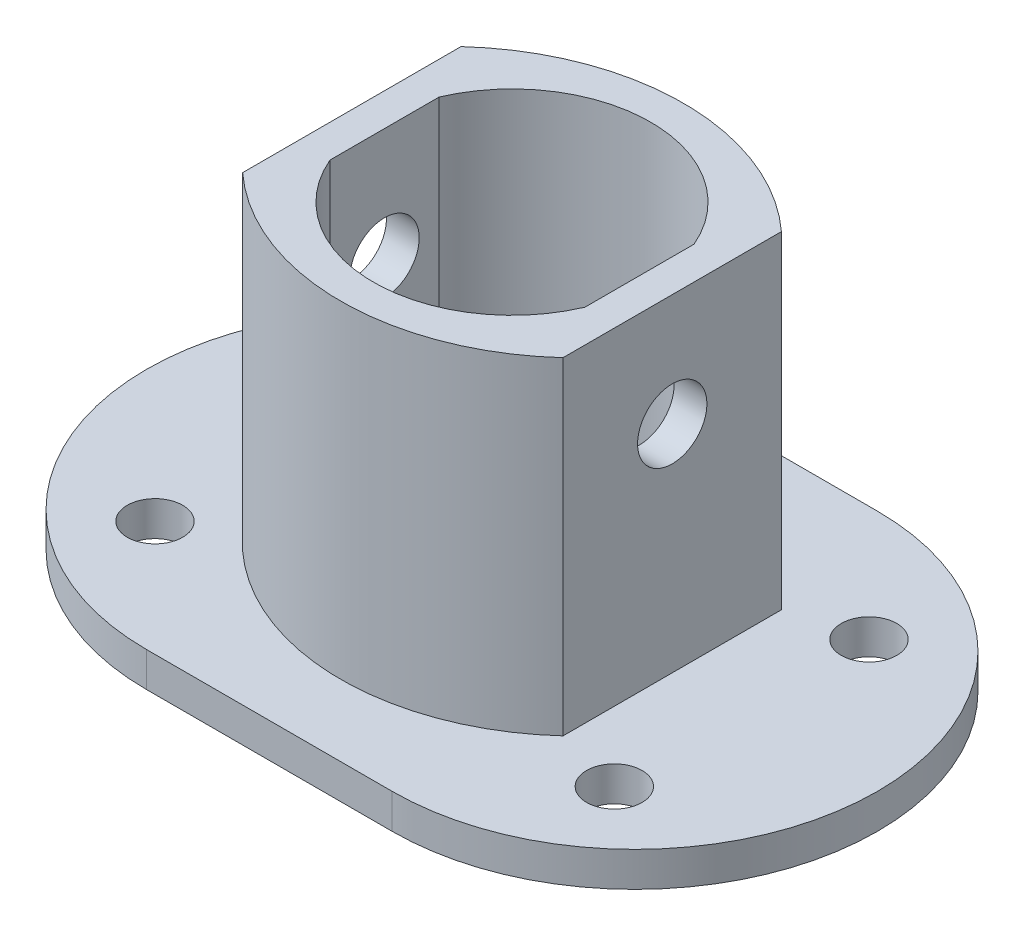
SolidWorks part; units mm, degrees
material "6061-T6 (SS)"
ref_plane "Front Plane" through (0, 0, 0) normal (0, 0, 1) x (1, 0, 0)
ref_plane "Top Plane" through (0, 0, 0) normal (0, 1, 0) x (1, 0, 0)
ref_plane "Right Plane" through (0, 0, 0) normal (1, 0, 0) x (0, 0, -1)
sketch "Sketch1" plane through (0, 0, 0) normal (0, 1, 0) x (1, 0, 0)
  line L0 (-11.25, 0) -> (11.25, 0) construction
  line L5 (-11.25, 22.225) -> (11.25, 22.225)
  line L6 (-11.25, -22.225) -> (11.25, -22.225)
  line L7 (-11.25, 22.225) -> (-11.25, -22.225) construction
  line L8 (11.25, 22.225) -> (11.25, -22.225) construction
  arc A0 (-11.25, 22.225) -> (-11.25, -22.225) centre (-11.25, 0) ccw
  arc A1 (11.25, -22.225) -> (11.25, 22.225) centre (11.25, 0) ccw
  point P2 (0, 0)
  dimension "D1" = 22.225
  dimension "D2" = 22.5
extrude "Boss-Extrude1" add sketch "Sketch1" along normal blind 3.175
sketch "Sketch2" plane through (0, 3.175, 0) normal (0, 1, 0) x (1, 0, 0)
  line L0 (-11.25, 22.225) -> (-11.25, -22.225) construction
  line L1 (-33.475, 0) -> (-26.475, 0) construction
  line L2 (-21.0364, -11.663) -> (-11.25, 0) construction
  line L3 (-11.25, 0) -> (-21.0364, 11.663) construction
  line L4 (0, 0) -> (0, 22.225) construction
  arc A0 (-11.25, 15.225) -> (-11.25, -15.225) centre (-11.25, 0) ccw construction
  arc A1 (-11.25, 22.225) -> (-11.25, -22.225) centre (-11.25, 0) ccw construction
  circle A2 centre (-21.0364, -11.663) radius 2.54
  circle A4 centre (-21.0364, 11.663) radius 2.54
  circle A6 centre (21.0364, -11.663) radius 2.54
  circle A7 centre (21.0364, 11.663) radius 2.54
  dimension "D2" = 5.08
  dimension "D1" = 7
  dimension "D3" = 100
extrude "Cut-Extrude1" cut sketch "Sketch2" against normal through all
sketch "Sketch3" plane through (0, 3.175, 0) normal (0, 1, 0) x (1, 0, 0)
  line L0 (-11.6743, 5) -> (-11.6743, -5)
  line L1 (-14.6743, 5.5816) -> (-14.6743, -5.5816) construction
  line L2 (-14.6743, 0) -> (-11.6743, 0) construction
  line L3 (0, 15.7) -> (0, 12.7) construction
  line L4 (-14.6743, -10) -> (-14.6743, 10)
  line L5 (14.6743, -10) -> (14.6743, 10)
  line L6 (11.6743, -5) -> (11.6743, 5)
  line L7 (11.6743, 0) -> (14.6743, 0) construction
  arc A0 (-14.6743, 5.5816) -> (-14.6743, -5.5816) centre (0, 0) ccw construction
  arc A1 (-11.6743, -5) -> (11.6743, -5) centre (0, 0) ccw
  arc A3 (11.6743, 5) -> (-11.6743, 5) centre (0, 0) ccw
  arc A4 (-14.6743, -10) -> (14.6743, -10) centre (0, 6.0391) ccw
  arc A5 (-14.6743, 10) -> (14.6743, 10) centre (0, -6.0391) cw
  point P13 (-14.6743, 0)
  dimension "D2" = 3
  dimension "D1" = 25.4
  dimension "D3" = 10
  dimension "D4" = 20
extrude "Boss-Extrude2" add sketch "Sketch3" along normal blind 30
sketch "Sketch4" plane through (0, 3.175, 0) normal (0, 1, 0) x (1, 0, 0)
  circle A0 centre (0, 0) radius 6.35
  dimension "D1" = 12.7
extrude "Cut-Extrude2" cut sketch "Sketch4" against normal through all
sketch "Sketch6" plane through (-14.6743, 2.2474, 9.5309) normal (-1, 0, 0) x (0, 0, 1)
  line L0 (-19.5309, 30.9276) -> (0.4691, 30.9276) construction
  circle A2 centre (-9.5309, 20.6776) radius 3.175
  point P5 (-9.5309, 30.9276)
  dimension "D1" = 10.25
  dimension "D2" = 6.35
extrude "Cut-Extrude3" cut sketch "Sketch6" against normal through all
sketch "Sketch8" plane through (0, 15.875, 0) normal (-1, 0, 0) x (0, 1, 0)
  line L0 (-12.7, 22.225) -> (2.3, 0)
  line L1 (-12.7, -22.225) -> (-12.7, 22.225) construction
  line L2 (2.3, 0) -> (2.3, -10)
  line L3 (2.3, -10) -> (-12.7, -10)
  line L4 (-12.7, 22.225) -> (-15.875, 22.225) construction
  line L6 (-12.7, -10) -> (-12.7, 22.225)
  line L10 (17.3, -15.7) -> (17.3, -10) construction
  line L12 (17.3, -10) -> (-12.7, -10) construction
  dimension "D2" = 10
  dimension "D3" = 15
extrude "Boss-Extrude3" [suppressed] add sketch "Sketch8" along normal mid plane 20
sketch "Sketch10" [suppressed] plane through (0, 18.175, 0) normal (0, 1, 0) x (0, 0, -1)
  line L1 (14.6743, 5) -> (24.6743, 5)
  line L2 (14.6743, 5) -> (14.6743, -5)
  line L3 (14.6743, -5) -> (24.6743, -5)
  line L4 (24.6743, 5) -> (24.6743, -5)
  line L7 (24.6743, 10) -> (24.6743, -10) construction
  line L8 (14.6743, -10) -> (24.6743, -10) construction
  line L9 (14.6743, -10) -> (14.6743, 10) construction
  dimension "D1" = 10
  dimension "D2" = 5
extrude "Cut-Extrude4" [suppressed] cut sketch "Sketch10" against normal blind 20
sketch "Sketch12" plane through (-14.6743, 2.2474, 9.5309) normal (-1, 0, 0) x (0, 0, 1)
  line L2 (-19.5309, 30.9276) -> (0.4691, 30.9276) construction
  circle A0 centre (-9.5309, 0.6776) radius 2.5
  circle A1 centre (-9.5309, 20.6776) radius 3.175 construction
  point P9 (-9.5309, 30.9276)
  dimension "D1" = 5
  dimension "D2" = 20
extrude "Boss-Extrude4" [suppressed] add sketch "Sketch12" along normal blind 3
fillet "Fillet1" [suppressed] radius 4
sketch "Sketch14" [suppressed] plane through (10, 0, 0) normal (1, 0, 0) x (0, 1, 0)
  line L0 (3.175, -14.6743) -> (18.175, -14.6743) construction
  line L1 (18.175, -14.6743) -> (18.175, -19.9682) construction
  circle A0 centre (15.175, -17.6743) radius 1.05
  dimension "D1" = 2.1
  dimension "D2" = 3
  dimension "D3" = 3
extrude "Cut-Extrude5" [suppressed] cut sketch "Sketch14" against normal blind 20
chamfer "Chamfer1" [suppressed] distance 0.2 angle 60
